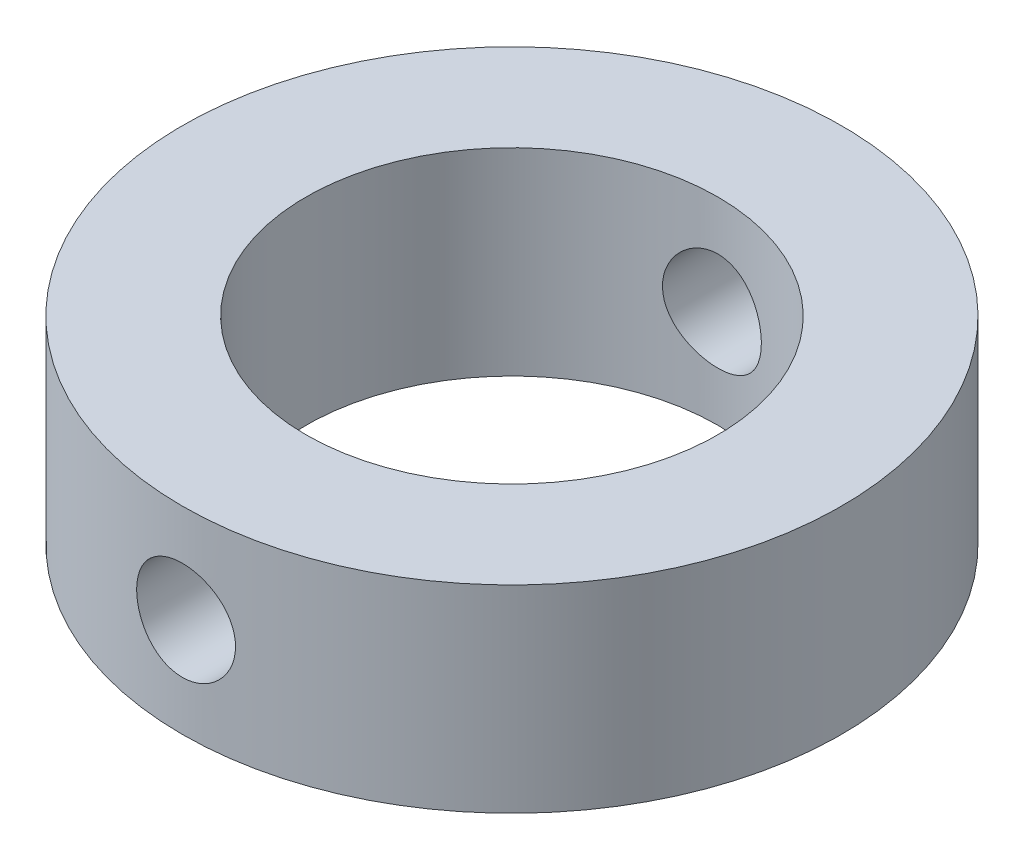
SolidWorks part; units mm, degrees
ref_plane "Front Plane" through (0, 0, 0) normal (0, 0, 1) x (1, 0, 0)
ref_plane "Top Plane" through (0, 0, 0) normal (0, 1, 0) x (1, 0, 0)
ref_plane "Right Plane" through (0, 0, 0) normal (1, 0, 0) x (0, 0, -1)
sketch "Sketch1" plane through (0, 0, 0) normal (0, 1, 0) x (1, 0, 0)
  circle A0 centre (0, 0) radius 12.5
  circle A1 centre (0, 0) radius 20
extrude "Boss-Extrude1" add sketch "Sketch1" along normal blind 12
ref_plane "Plane1" through (0, 0, 20) normal (0, 0, 1) x (1, 0, 0)
sketch "Sketch3" plane through (0, 0, 20) normal (0, 0, 1) x (1, 0, 0)
  line L0 (0, 0) -> (0, 12)
  line L1 (20, 12) -> (-20, 12) construction
  circle A0 centre (0, 6) radius 3
extrude "Cut-Extrude1" cut sketch "Sketch3" against normal blind 62 contours L0 A0 | L0 A0
